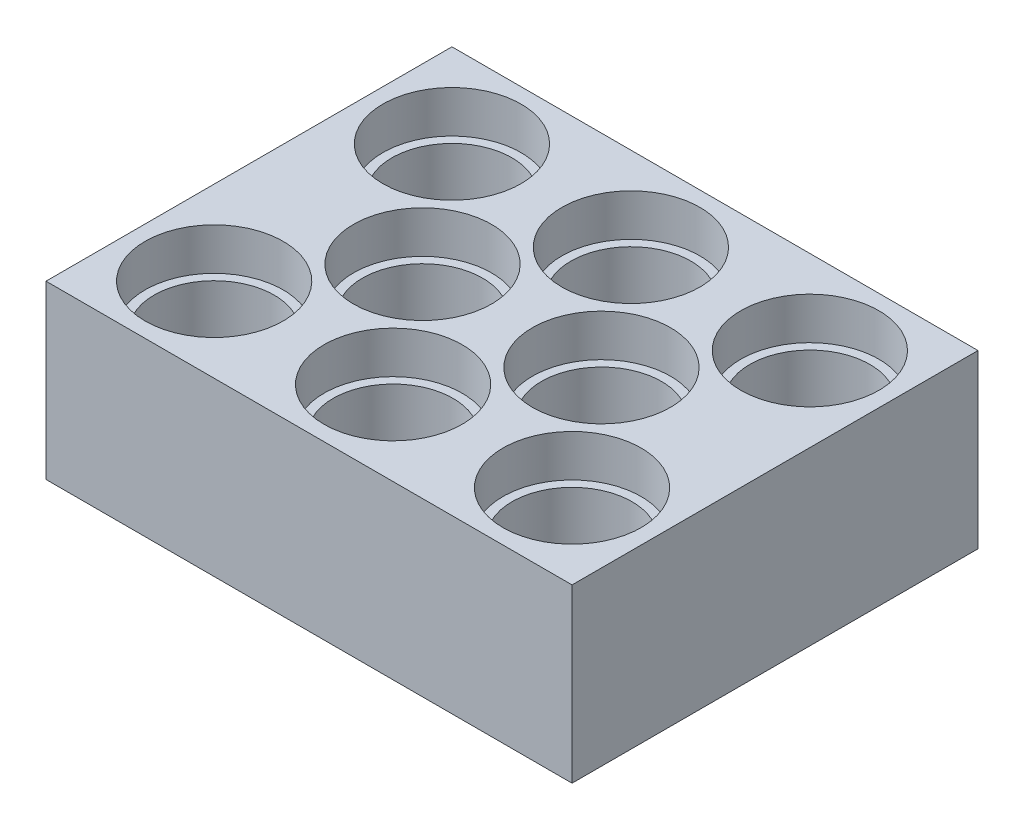
SolidWorks part; units mm, degrees
ref_plane "Спереди" through (0, 0, 0) normal (0, 0, 1) x (1, 0, 0)
ref_plane "Сверху" through (0, 0, 0) normal (0, 1, 0) x (1, 0, 0)
ref_plane "Справа" through (0, 0, 0) normal (1, 0, 0) x (0, 0, -1)
sketch "Эскиз1" plane through (0, 0, 0) normal (0, 1, 0) x (1, 0, 0)
  line L1 (-219, -169) -> (219, -169)
  line L2 (-219, -169) -> (-219, 169)
  line L3 (-219, 169) -> (219, 169)
  line L4 (219, -169) -> (219, 169)
  line L5 (-219, -169) -> (219, 169) construction
  line L6 (-219, 169) -> (219, -169) construction
  point P0 (0, 0)
  dimension "D1" = 338
  dimension "D2" = 438
extrude "Бобышка-Вытянуть1" add sketch "Эскиз1" along normal blind 143
sketch "Эскиз2" plane through (0, 143, 0) normal (0, 1, 0) x (1, 0, 0)
  line L0 (0, 99) -> (-149, -99) construction
  line L1 (-149, 99) -> (0, -99) construction
  line L2 (-219, 169) -> (-219, -169) construction
  line L3 (219, -169) -> (219, 169) construction
  line L4 (219, 169) -> (-219, 169) construction
  line L5 (-219, -169) -> (219, -169) construction
  line L6 (0, 99) -> (149, -99) construction
  line L7 (149, 99) -> (0, -99) construction
  circle A0 centre (-149, 99) radius 50
  circle A1 centre (0, 99) radius 50
  circle A2 centre (0, -99) radius 50
  circle A3 centre (-149, -99) radius 50
  circle A4 centre (-74.5, 0) radius 50
  circle A5 centre (149, 99) radius 50
  circle A6 centre (149, -99) radius 50
  circle A7 centre (74.5, 0) radius 50
  dimension "D1" = 100
  dimension "D2" = 3
  dimension "D4" = 149
  dimension "D6" = 70
  dimension "D7" = 70
  dimension "D8" = 70
  dimension "D9" = 70
  dimension "D10" = 70
  dimension "D3" = 2
extrude "Вырез-Вытянуть1" cut sketch "Эскиз2" against normal blind 135
sketch "Эскиз4" plane through (0, 143, 0) normal (0, 1, 0) x (1, 0, 0)
  line L0 (0, 99) -> (-149, -99) construction
  line L1 (-149, 99) -> (0, -99) construction
  line L2 (0, 99) -> (149, -99) construction
  line L3 (149, 99) -> (0, -99) construction
  line L4 (219, 169) -> (-219, 169) construction
  line L5 (-219, -169) -> (219, -169) construction
  line L6 (-219, 169) -> (-219, -169) construction
  line L7 (219, -169) -> (219, 169) construction
  circle A0 centre (-149, 99) radius 57.5
  circle A1 centre (0, 99) radius 57.5
  circle A2 centre (0, -99) radius 57.5
  circle A3 centre (-149, -99) radius 57.5
  circle A4 centre (-74.5, 0) radius 57.5
  circle A5 centre (149, 99) radius 57.5
  circle A6 centre (149, -99) radius 57.5
  circle A7 centre (74.5, 0) radius 57.5
  dimension "D1" = 70
  dimension "D2" = 70
  dimension "D3" = 115
  dimension "D4" = 70
  dimension "D5" = 70
  dimension "D6" = 70
  dimension "D7" = 70
  dimension "D8" = 70
  dimension "D9" = 70
extrude "Вырез-Вытянуть2" cut sketch "Эскиз4" against normal blind 35
